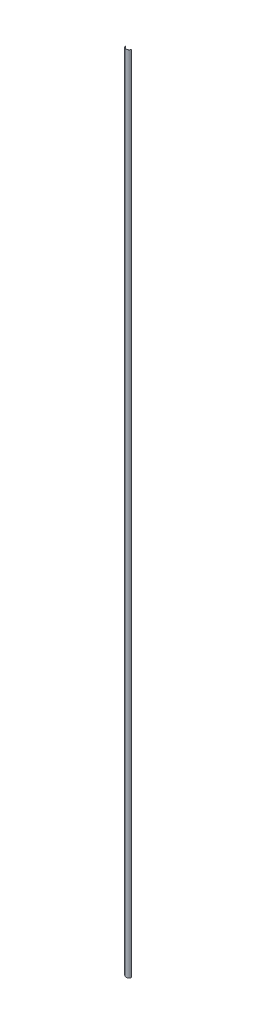
SolidWorks part; units mm, degrees
material "AISI 1045 Steel, cold drawn"
ref_plane "Front Plane" through (0, 0, 0) normal (0, 0, 1) x (1, 0, 0)
ref_plane "Top Plane" through (0, 0, 0) normal (0, 1, 0) x (1, 0, 0)
ref_plane "Right Plane" through (0, 0, 0) normal (1, 0, 0) x (0, 0, -1)
sketch "Sketch1" plane through (0, 0, 0) normal (0, 1, 0) x (1, 0, 0)
  line L1 (-45, -45) -> (45, -45)
  line L2 (-45, -45) -> (-45, 45)
  line L3 (-45, 45) -> (45, 45)
  line L4 (45, -45) -> (45, 45)
  line L5 (-45, -45) -> (45, 45) construction
  line L6 (-45, 45) -> (45, -45) construction
  point P0 (0, 0)
  dimension "D1" = 90
  dimension "D2" = 90
extrude "Boss-Extrude1" add sketch "Sketch1" along normal blind 5
sketch "Sketch2" plane through (0, 0, 0) normal (0, -1, 0) x (1, 0, 0)
  line L0 (-7.5197, 1.9769) -> (-7.4197, 1.9769)
  line L1 (7.3798, 2.121) -> (7.4803, 2.121)
  arc A0 (-7.5197, 1.9769) -> (7.4803, 2.121) centre (0, 0) cw
  arc A1 (-7.4197, 1.9769) -> (7.3798, 2.121) centre (0, 0) cw
  dimension "D1" = 15
  dimension "D2" = 0.1
extrude "Boss-Extrude2" add sketch "Sketch2" along normal blind 2005
sketch "Sketch3" plane through (0, 5, 0) normal (0, 1, 0) x (1, 0, 0)
  line L1 (-45, 45) -> (45, 45)
  line L2 (-45, 45) -> (-45, -45)
  line L3 (-45, -45) -> (45, -45)
  line L4 (45, 45) -> (45, -45)
extrude "Cut-Extrude3" cut sketch "Sketch3" against normal blind 5
